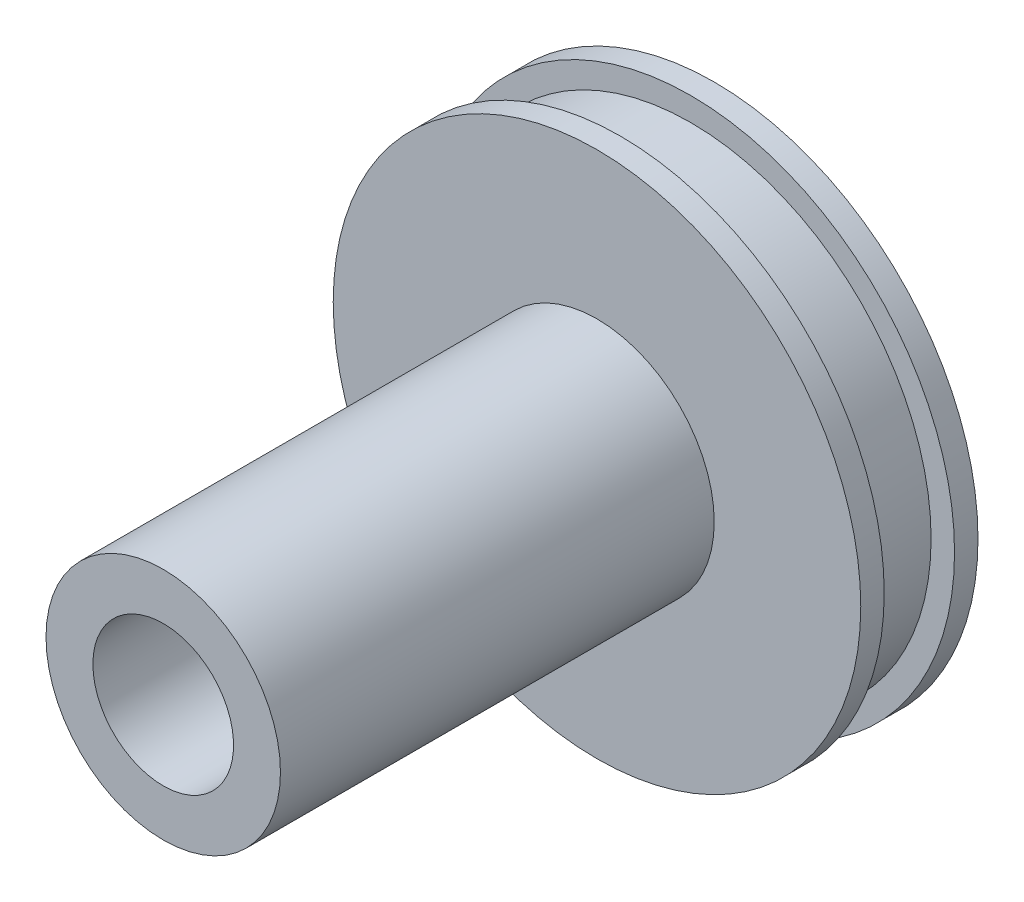
SolidWorks part; units mm, degrees
ref_plane "Vorne" through (0, 0, 0) normal (0, 0, 1) x (1, 0, 0)
ref_plane "Oben" through (0, 0, 0) normal (0, 1, 0) x (1, 0, 0)
ref_plane "Rechts" through (0, 0, 0) normal (1, 0, 0) x (0, 0, -1)
ref_plane "E_Boden" through (0, 1, 0) normal (0, 1, 0) x (1, 0, 0)
sketch "Skizze1" plane through (0, 0, 0) normal (0, 0, 1) x (1, 0, 0)
  line L0 (0, -37.3227) -> (0, 48.2798) construction
  line L1 (-67.1123, 0) -> (65.2861, 0) construction
  circle A0 centre (0, 0) radius 22.5
  dimension "D1" = 45
extrude "Seite1" add sketch "Skizze1" along normal blind 2
sketch "Skizze2" plane through (0, 0, 0) normal (0, 0, 1) x (1, 0, 0)
  circle A0 centre (0, 0) radius 20.5
  dimension "D1" = 41
extrude "Lauffläche" add sketch "Skizze2" along normal blind 8
sketch "Skizze5" plane through (0, 0, 8) normal (0, 0, 1) x (1, 0, 0)
  circle A0 centre (0, 0) radius 22.5
extrude "Seite 2" add sketch "Skizze5" along normal blind 2
sketch "Skizze7" plane through (0, 0, 0) normal (0, 0, 1) x (1, 0, 0)
  circle A0 centre (0, 0) radius 2.5
  dimension "D1" = 5
extrude "Bohrung" cut sketch "Skizze7" along normal blind 100 and the other way through all
sketch "Skizze9" plane through (0, 0, 10) normal (0, 0, 1) x (1, 0, 0)
  circle A0 centre (0, 0) radius 10
  dimension "D1" = 20
extrude "Zapfen" add sketch "Skizze9" along normal blind 37
hole_wizard "Ø12.0 (12) Durchmesser Bohrung1" positions "Skizze15" profile "Skizze17" hole size "Ø12.0" standard "DIN" end condition through all
sketch "Skizze15" plane through (0, 0, 0) normal (0, 0, -1) x (-1, 0, 0)
  point P0 (0, 0)
sketch "Skizze17" plane through (0, 0, 0) normal (1, 0, 0) x (0, 1, 0)
  line L0 (0, 0) -> (0, 47)
  line L1 (0, 47) -> (6, 47)
  line L2 (6, 47) -> (6, 0)
  line L5 (6, 0) -> (0, 0)
  line L11 (0, -6.35) -> (0, 107.95) construction
  dimension "Bohrerdurchmesser" = 12
  dimension "Bohrungstiefe" = 47
